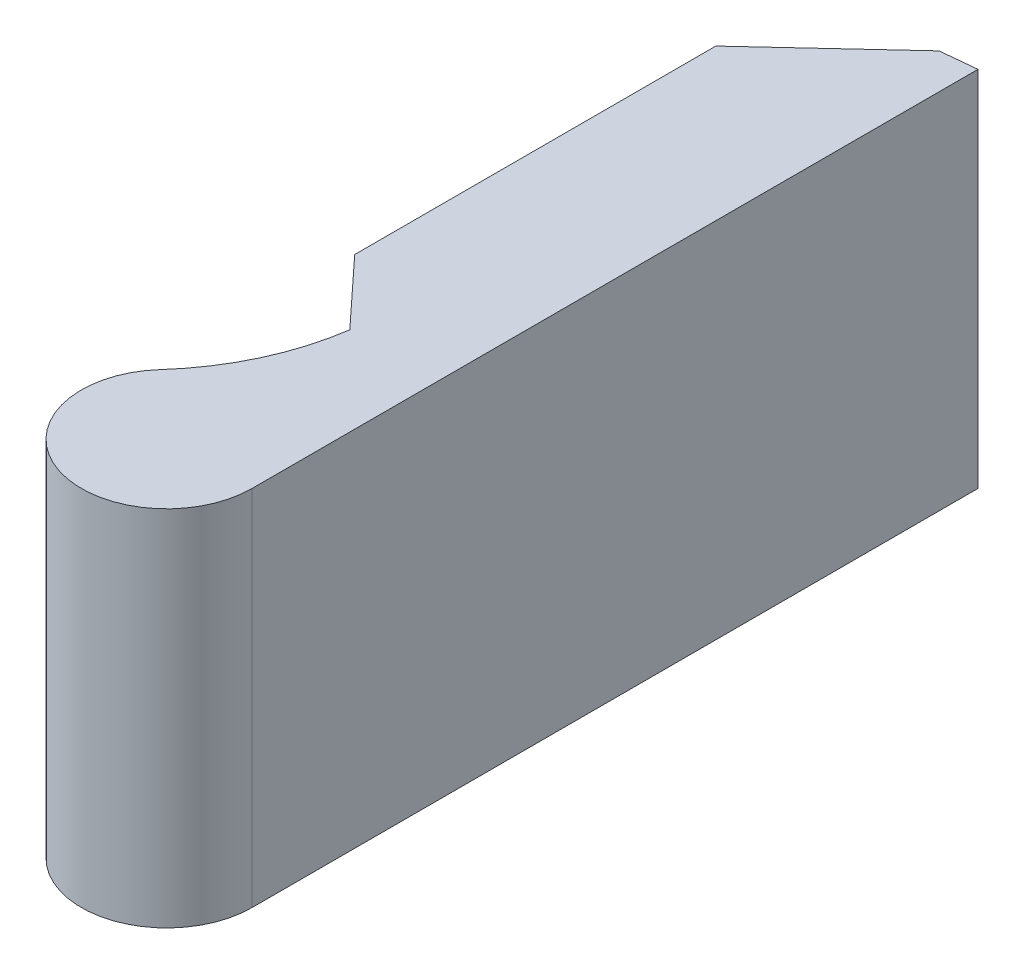
SolidWorks part; units mm, degrees
ref_plane "Front Plane" through (0, 0, 0) normal (0, 0, 1) x (1, 0, 0)
ref_plane "Top Plane" through (0, 0, 0) normal (0, 1, 0) x (1, 0, 0)
ref_plane "Right Plane" through (0, 0, 0) normal (1, 0, 0) x (0, 0, -1)
sketch "Sketch1" plane through (0, 0, 0) normal (0, 1, 0) x (1, 0, 0)
  line L0 (0, 8.4678) -> (0, -3.5322)
  line L1 (-1.4639, -0.4521) -> (-2.5, 0.6649)
  line L2 (-2.5, 0.6649) -> (-2.5, 6.6343)
  line L3 (-2.5, 6.6343) -> (-0.5862, 8.4095)
  line L4 (-0.5862, 8.4095) -> (0, 8.4678)
  arc A0 (0, -3.5322) -> (-2.4606, -2.5898) centre (-1.4108, -3.5322) cw
  arc A1 (-2.4606, -2.5898) -> (-1.4639, -0.4521) centre (-5.4766, 0.1176) ccw
  point P0 (-0.8804, 8.4095)
  point P7 (0, 8.7502)
  dimension "D1" = 12
  dimension "D2" = 2.5
extrude "Boss-Extrude1" add sketch "Sketch1" along normal blind 6
